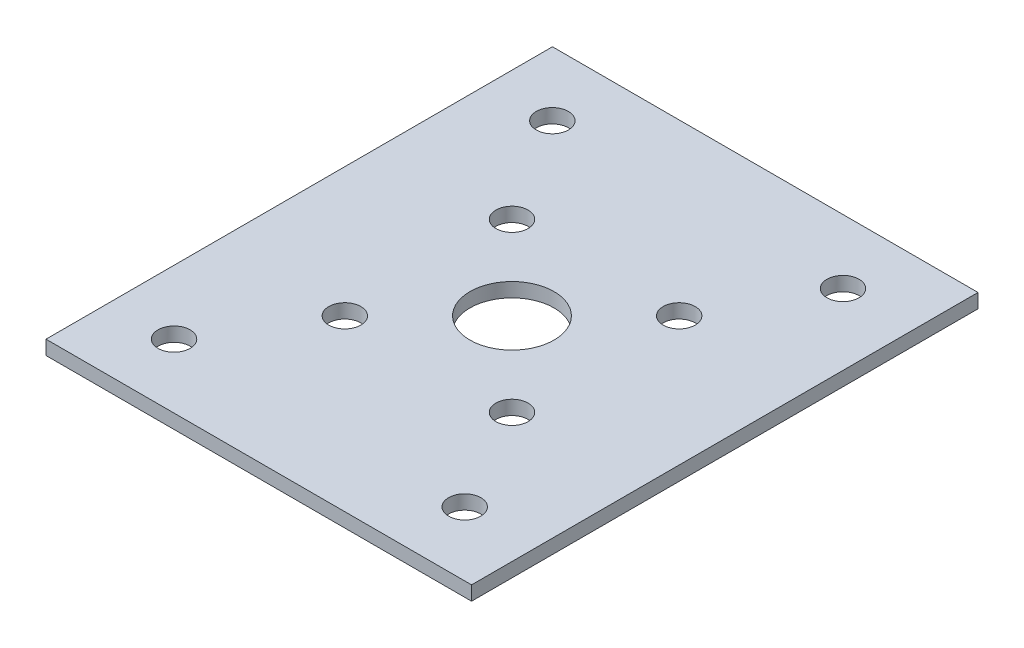
SolidWorks part; units mm, degrees
material "Thornel Mat VMA"
ref_plane "Front Plane" through (0, 0, 0) normal (0, 0, 1) x (1, 0, 0)
ref_plane "Top Plane" through (0, 0, 0) normal (0, 1, 0) x (1, 0, 0)
ref_plane "Right Plane" through (0, 0, 0) normal (1, 0, 0) x (0, 0, -1)
sketch "Sketch2" plane through (0, 0, 0) normal (0, 1, 0) x (1, 0, 0)
  line L1 (-22.5, -26.778) -> (22.5, -26.778)
  line L2 (-22.5, -26.778) -> (-22.5, 26.778)
  line L3 (-22.5, 26.778) -> (22.5, 26.778)
  line L4 (22.5, -26.778) -> (22.5, 26.778)
  point P0 (0, 0)
  point P6 (22.5, 0)
  dimension "D1" = 53.556
  dimension "D2" = 45
  dimension "D3" = 22.5
extrude "Boss-Extrude1" add sketch "Sketch2" along normal blind 1.5
hole_wizard "M3 Clearance Hole" positions "Sketch7" profile "Sketch8" hole size "M3" standard "ANSI Metric" end condition up to next
sketch "Sketch7" plane through (0, 1.5, 0) normal (0, 1, 0) x (1, 0, 0)
  point P0 (-15.7366, 20)
  point P2 (15, 20)
  point P4 (15, -20)
  point P6 (-15.7366, -20)
  point P16 (0, 0)
  dimension "D1" = 20
  dimension "D2" = 30.7366
  dimension "D3" = 40
  dimension "D4" = 15
sketch "Sketch8" plane through (-15.7366, 1.5, -20) normal (1, 0, 0) x (0, 0, 1)
  line L0 (0, 0) -> (0, 1.5)
  line L1 (0, 1.5) -> (1.7, 1.5)
  line L2 (1.7, 1.5) -> (1.7, 0)
  line L5 (1.7, 0) -> (0, 0)
  line L11 (0, -6.35) -> (0, 107.95) construction
  dimension "Thru Hole Dia." = 3.4
  dimension "Thru Hole Depth" = 1.5
hole_wizard "M3 Clearance Slot1" positions "Sketch11" profile "Sketch12" size "M3" standard "ANSI Metric"
sketch "Sketch11" plane through (0, 1.5, 0) normal (0, 1, 0) x (1, 0, 0)
  line L1 (-7.4246, 7.4246) -> (-2.4749, 2.4749) construction
  line L2 (-22.5, 25) -> (-22.5, -25) construction
  line L3 (-2.4749, 2.4749) -> (4.9497, -4.9497) construction
  point P0 (-4.9497, 4.9497)
  point P13 (4.9497, -4.9497)
  dimension "D1" = 7
  dimension "D2" = 45
  dimension "D3" = 7
  dimension "D4" = 7
sketch "Sketch12" plane through (-4.9497, 1.5, -4.9497) normal (1, 0, 0) x (0, 0, 1)
  line L0 (0, 0) -> (0, 1.5)
  line L1 (0, 1.5) -> (1.7, 1.5)
  line L2 (1.7, 1.5) -> (1.7, 0)
  line L5 (1.7, 0) -> (0, 0)
  line L11 (0, -6.35) -> (0, 107.95) construction
  dimension "Thru Hole Dia." = 3.4
  dimension "Thru Hole Depth" = 1.5
hole_wizard "M3 Clearance Slot2" positions "Sketch13" profile "Sketch14" size "M3" standard "ANSI Metric"
sketch "Sketch13" plane through (0, 1.5, 0) normal (0, 1, 0) x (1, 0, 0)
  line L0 (2.4749, 2.4749) -> (7.4246, 7.4246) construction
  line L1 (22.5, -25) -> (22.5, 25) construction
  line L2 (2.4749, 2.4749) -> (-4.9497, -4.9497) construction
  point P0 (4.9497, 4.9497)
  point P4 (-4.9497, -4.9497)
  dimension "D1" = 7
  dimension "D2" = 45
  dimension "D3" = 7
  dimension "D4" = 7
sketch "Sketch14" plane through (4.9497, 1.5, -4.9497) normal (1, 0, 0) x (0, 0, 1)
  line L0 (0, 0) -> (0, 1.5)
  line L1 (0, 1.5) -> (1.7, 1.5)
  line L2 (1.7, 1.5) -> (1.7, 0)
  line L5 (1.7, 0) -> (0, 0)
  line L11 (0, -6.35) -> (0, 107.95) construction
  dimension "Thru Hole Dia." = 3.4
  dimension "Thru Hole Depth" = 1.5
hole_wizard "M3 Clearance Hole1" positions "Sketch15" profile "Sketch16" hole size "M3" standard "ANSI Metric" end condition through all
sketch "Sketch15" plane through (0, 1.5, 0) normal (0, 1, 0) x (1, 0, 0)
  line L0 (-8.8388, -8.8388) -> (8.8388, 8.8388) construction
  line L2 (-8.8388, 8.8388) -> (8.8388, -8.8388) construction
  line L4 (0, 0) -> (0, 12.5) construction
  circle A0 centre (0, 0) radius 12.5 construction
  point P7 (-8.8388, 8.8388)
  point P9 (8.8388, -8.8388)
  point P11 (8.8388, 8.8388)
  point P13 (-8.8388, -8.8388)
  dimension "D1" = 25
  dimension "D2" = 45
  dimension "D3" = 45
sketch "Sketch16" plane through (-8.8388, 1.5, 8.8388) normal (1, 0, 0) x (0, 0, 1)
  line L0 (0, 0) -> (0, 1.5)
  line L1 (0, 1.5) -> (1.7, 1.5)
  line L2 (1.7, 1.5) -> (1.7, 0)
  line L5 (1.7, 0) -> (0, 0)
  line L11 (0, -6.35) -> (0, 107.95) construction
  dimension "Thru Hole Dia." = 3.4
  dimension "Thru Hole Depth" = 1.5
sketch "Sketch17" plane through (0, 1.5, 0) normal (0, 1, 0) x (1, 0, 0)
  circle A0 centre (0, 0) radius 4.445
  dimension "D1" = 8.89
extrude "Cut-Extrude1" cut sketch "Sketch17" against normal up to next
